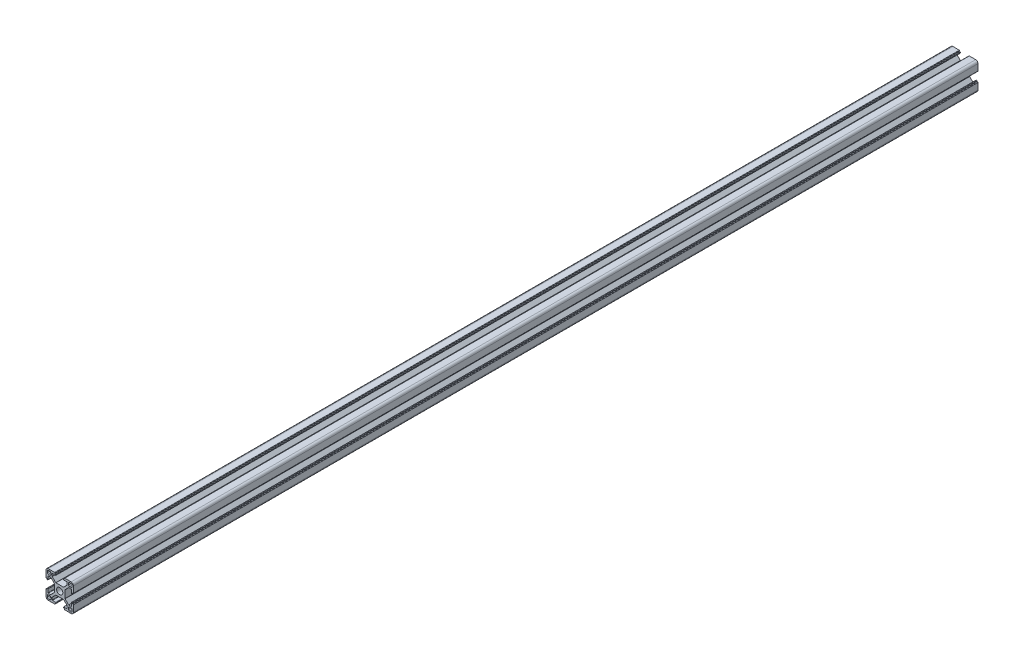
SolidWorks part; units mm, degrees
ref_plane "Front Plane" through (0, 0, 0) normal (0, 0, 1) x (1, 0, 0)
ref_plane "Top Plane" through (0, 0, 0) normal (0, 1, 0) x (1, 0, 0)
ref_plane "Right Plane" through (0, 0, 0) normal (1, 0, 0) x (0, 0, -1)
sketch "Model" plane through (0, 0, 0) normal (0, 0, 1) x (1, 0, 0)
  line L0 (21.5, 27) -> (25, 27)
  line L1 (27, 25) -> (27, 21.5)
  line L2 (25, 19.5) -> (21.5, 19.5)
  line L3 (19.5, 21.5) -> (19.5, 25)
  line L4 (21.5, -27) -> (25, -27)
  line L5 (27, -25) -> (27, -21.5)
  line L6 (25, -19.5) -> (21.5, -19.5)
  line L7 (19.5, -21.5) -> (19.5, -25)
  line L8 (0, 11.6) -> (-8.2402, 11.6)
  line L9 (-8.6645, 11.7757) -> (-16.3243, 19.4355)
  line L10 (-16.5, 19.8598) -> (-16.5, 25)
  line L11 (-15.9, 25.6) -> (-8.8, 25.6)
  line L12 (-8.2, 26.2) -> (-8.2, 27.4)
  line L13 (-8.8, 28) -> (-9.8, 28)
  line L14 (-10.4, 28.6) -> (-10.4, 29.4)
  line L15 (-11, 30) -> (-25, 30)
  line L16 (-30, 25) -> (-30, 11)
  line L17 (-29.4, 10.4) -> (-28.6, 10.4)
  line L18 (-28, 9.8) -> (-28, 8.8)
  line L19 (-27.4, 8.2) -> (-26.2, 8.2)
  line L20 (-25.6, 8.8) -> (-25.6, 15.9)
  line L21 (-25, 16.5) -> (-19.8598, 16.5)
  line L22 (-19.4355, 16.3243) -> (-11.7757, 8.6645)
  line L23 (-11.6, 8.2402) -> (-11.6, 0)
  line L24 (-11.6, 0) -> (-11.6, -8.2402)
  line L25 (-11.7757, -8.6645) -> (-19.4355, -16.3243)
  line L26 (-19.8598, -16.5) -> (-25, -16.5)
  line L27 (-25.6, -15.9) -> (-25.6, -8.8)
  line L28 (-26.2, -8.2) -> (-27.4, -8.2)
  line L29 (-28, -8.8) -> (-28, -9.8)
  line L30 (-28.6, -10.4) -> (-29.4, -10.4)
  line L31 (-30, -11) -> (-30, -25)
  line L32 (-25, -30) -> (-11, -30)
  line L33 (-10.4, -29.4) -> (-10.4, -28.6)
  line L34 (-9.8, -28) -> (-8.8, -28)
  line L35 (-8.2, -27.4) -> (-8.2, -26.2)
  line L36 (-8.8, -25.6) -> (-15.9, -25.6)
  line L37 (-16.5, -25) -> (-16.5, -19.8598)
  line L38 (-16.3243, -19.4355) -> (-8.6645, -11.7757)
  line L39 (-8.2402, -11.6) -> (0, -11.6)
  line L40 (0, -11.6) -> (8.2402, -11.6)
  line L41 (8.6645, -11.7757) -> (16.3243, -19.4355)
  line L42 (16.5, -19.8598) -> (16.5, -25)
  line L43 (15.9, -25.6) -> (8.8, -25.6)
  line L44 (8.2, -26.2) -> (8.2, -27.4)
  line L45 (8.8, -28) -> (9.8, -28)
  line L46 (10.4, -28.6) -> (10.4, -29.4)
  line L47 (11, -30) -> (25, -30)
  line L48 (30, -25) -> (30, -11)
  line L49 (29.4, -10.4) -> (28.6, -10.4)
  line L50 (28, -9.8) -> (28, -8.8)
  line L51 (27.4, -8.2) -> (26.2, -8.2)
  line L52 (25.6, -8.8) -> (25.6, -15.9)
  line L53 (25, -16.5) -> (19.8598, -16.5)
  line L54 (19.4355, -16.3243) -> (11.7757, -8.6645)
  line L55 (11.6, -8.2402) -> (11.6, 0)
  line L56 (11.6, 0) -> (11.6, 8.2402)
  line L57 (11.7757, 8.6645) -> (19.6113, 16.5)
  line L58 (19.6113, 16.5) -> (25, 16.5)
  line L59 (25.6, 15.9) -> (25.6, 8.8)
  line L60 (26.2, 8.2) -> (27.4, 8.2)
  line L61 (28, 8.8) -> (28, 9.8)
  line L62 (28.6, 10.4) -> (29.4, 10.4)
  line L63 (30, 11) -> (30, 25)
  line L64 (25, 30) -> (11, 30)
  line L65 (10.4, 29.4) -> (10.4, 28.6)
  line L66 (9.8, 28) -> (8.8, 28)
  line L67 (8.2, 27.4) -> (8.2, 26.2)
  line L68 (8.8, 25.6) -> (15.9, 25.6)
  line L69 (16.5, 25) -> (16.5, 19.8598)
  line L70 (16.3243, 19.4355) -> (8.6645, 11.7757)
  line L71 (8.2402, 11.6) -> (0, 11.6)
  line L72 (-21.5, -27) -> (-25, -27)
  line L73 (-27, -25) -> (-27, -21.5)
  line L74 (-25, -19.5) -> (-21.5, -19.5)
  line L75 (-19.5, -21.5) -> (-19.5, -25)
  line L76 (-21.5, 27) -> (-25, 27)
  line L77 (-27, 25) -> (-27, 21.5)
  line L78 (-25, 19.5) -> (-21.5, 19.5)
  line L79 (-19.5, 21.5) -> (-19.5, 25)
  circle A0 centre (0, 0) radius 6.8
  arc A1 (21.5, 27) -> (19.5, 25) centre (21.5, 25) ccw
  arc A2 (27, 25) -> (25, 27) centre (25, 25) ccw
  arc A3 (25, 19.5) -> (27, 21.5) centre (25, 21.5) ccw
  arc A4 (19.5, 21.5) -> (21.5, 19.5) centre (21.5, 21.5) ccw
  arc A5 (19.5, -25) -> (21.5, -27) centre (21.5, -25) ccw
  arc A6 (25, -27) -> (27, -25) centre (25, -25) ccw
  arc A7 (27, -21.5) -> (25, -19.5) centre (25, -21.5) ccw
  arc A8 (21.5, -19.5) -> (19.5, -21.5) centre (21.5, -21.5) ccw
  arc A9 (-8.6645, 11.7757) -> (-8.2402, 11.6) centre (-8.2402, 12.2) ccw
  arc A10 (-16.5, 19.8598) -> (-16.3243, 19.4355) centre (-15.9, 19.8598) ccw
  arc A11 (-15.9, 25.6) -> (-16.5, 25) centre (-15.9, 25) ccw
  arc A12 (-8.8, 25.6) -> (-8.2, 26.2) centre (-8.8, 26.2) ccw
  arc A13 (-8.2, 27.4) -> (-8.8, 28) centre (-8.8, 27.4) ccw
  arc A14 (-10.4, 28.6) -> (-9.8, 28) centre (-9.8, 28.6) ccw
  arc A15 (-10.4, 29.4) -> (-11, 30) centre (-11, 29.4) ccw
  arc A16 (-25, 30) -> (-30, 25) centre (-25, 25) ccw
  arc A17 (-30, 11) -> (-29.4, 10.4) centre (-29.4, 11) ccw
  arc A18 (-28, 9.8) -> (-28.6, 10.4) centre (-28.6, 9.8) ccw
  arc A19 (-28, 8.8) -> (-27.4, 8.2) centre (-27.4, 8.8) ccw
  arc A20 (-26.2, 8.2) -> (-25.6, 8.8) centre (-26.2, 8.8) ccw
  arc A21 (-25, 16.5) -> (-25.6, 15.9) centre (-25, 15.9) ccw
  arc A22 (-19.4355, 16.3243) -> (-19.8598, 16.5) centre (-19.8598, 15.9) ccw
  arc A23 (-11.6, 8.2402) -> (-11.7757, 8.6645) centre (-12.2, 8.2402) ccw
  arc A24 (-11.7757, -8.6645) -> (-11.6, -8.2402) centre (-12.2, -8.2402) ccw
  arc A25 (-19.8598, -16.5) -> (-19.4355, -16.3243) centre (-19.8598, -15.9) ccw
  arc A26 (-25.6, -15.9) -> (-25, -16.5) centre (-25, -15.9) ccw
  arc A27 (-25.6, -8.8) -> (-26.2, -8.2) centre (-26.2, -8.8) ccw
  arc A28 (-27.4, -8.2) -> (-28, -8.8) centre (-27.4, -8.8) ccw
  arc A29 (-28.6, -10.4) -> (-28, -9.8) centre (-28.6, -9.8) ccw
  arc A30 (-29.4, -10.4) -> (-30, -11) centre (-29.4, -11) ccw
  arc A31 (-30, -25) -> (-25, -30) centre (-25, -25) ccw
  arc A32 (-11, -30) -> (-10.4, -29.4) centre (-11, -29.4) ccw
  arc A33 (-9.8, -28) -> (-10.4, -28.6) centre (-9.8, -28.6) ccw
  arc A34 (-8.8, -28) -> (-8.2, -27.4) centre (-8.8, -27.4) ccw
  arc A35 (-8.2, -26.2) -> (-8.8, -25.6) centre (-8.8, -26.2) ccw
  arc A36 (-16.5, -25) -> (-15.9, -25.6) centre (-15.9, -25) ccw
  arc A37 (-16.3243, -19.4355) -> (-16.5, -19.8598) centre (-15.9, -19.8598) ccw
  arc A38 (-8.2402, -11.6) -> (-8.6645, -11.7757) centre (-8.2402, -12.2) ccw
  arc A39 (8.6645, -11.7757) -> (8.2402, -11.6) centre (8.2402, -12.2) ccw
  arc A40 (16.5, -19.8598) -> (16.3243, -19.4355) centre (15.9, -19.8598) ccw
  arc A41 (15.9, -25.6) -> (16.5, -25) centre (15.9, -25) ccw
  arc A42 (8.8, -25.6) -> (8.2, -26.2) centre (8.8, -26.2) ccw
  arc A43 (8.2, -27.4) -> (8.8, -28) centre (8.8, -27.4) ccw
  arc A44 (10.4, -28.6) -> (9.8, -28) centre (9.8, -28.6) ccw
  arc A45 (10.4, -29.4) -> (11, -30) centre (11, -29.4) ccw
  arc A46 (25, -30) -> (30, -25) centre (25, -25) ccw
  arc A47 (30, -11) -> (29.4, -10.4) centre (29.4, -11) ccw
  arc A48 (28, -9.8) -> (28.6, -10.4) centre (28.6, -9.8) ccw
  arc A49 (28, -8.8) -> (27.4, -8.2) centre (27.4, -8.8) ccw
  arc A50 (26.2, -8.2) -> (25.6, -8.8) centre (26.2, -8.8) ccw
  arc A51 (25, -16.5) -> (25.6, -15.9) centre (25, -15.9) ccw
  arc A52 (19.4355, -16.3243) -> (19.8598, -16.5) centre (19.8598, -15.9) ccw
  arc A53 (11.6, -8.2402) -> (11.7757, -8.6645) centre (12.2, -8.2402) ccw
  arc A54 (11.7757, 8.6645) -> (11.6, 8.2402) centre (12.2, 8.2402) ccw
  arc A55 (25.6, 15.9) -> (25, 16.5) centre (25, 15.9) ccw
  arc A56 (25.6, 8.8) -> (26.2, 8.2) centre (26.2, 8.8) ccw
  arc A57 (27.4, 8.2) -> (28, 8.8) centre (27.4, 8.8) ccw
  arc A58 (28.6, 10.4) -> (28, 9.8) centre (28.6, 9.8) ccw
  arc A59 (29.4, 10.4) -> (30, 11) centre (29.4, 11) ccw
  arc A60 (30, 25) -> (25, 30) centre (25, 25) ccw
  arc A61 (11, 30) -> (10.4, 29.4) centre (11, 29.4) ccw
  arc A62 (9.8, 28) -> (10.4, 28.6) centre (9.8, 28.6) ccw
  arc A63 (8.8, 28) -> (8.2, 27.4) centre (8.8, 27.4) ccw
  arc A64 (8.2, 26.2) -> (8.8, 25.6) centre (8.8, 26.2) ccw
  arc A65 (16.5, 25) -> (15.9, 25.6) centre (15.9, 25) ccw
  arc A66 (16.3243, 19.4355) -> (16.5, 19.8598) centre (15.9, 19.8598) ccw
  arc A67 (8.2402, 11.6) -> (8.6645, 11.7757) centre (8.2402, 12.2) ccw
  arc A68 (-21.5, -27) -> (-19.5, -25) centre (-21.5, -25) ccw
  arc A69 (-27, -25) -> (-25, -27) centre (-25, -25) ccw
  arc A70 (-25, -19.5) -> (-27, -21.5) centre (-25, -21.5) ccw
  arc A71 (-19.5, -21.5) -> (-21.5, -19.5) centre (-21.5, -21.5) ccw
  arc A72 (-19.5, 25) -> (-21.5, 27) centre (-21.5, 25) ccw
  arc A73 (-25, 27) -> (-27, 25) centre (-25, 25) ccw
  arc A74 (-27, 21.5) -> (-25, 19.5) centre (-25, 21.5) ccw
  arc A75 (-21.5, 19.5) -> (-19.5, 21.5) centre (-21.5, 21.5) ccw
extrude "Boss-Extrude1" add sketch "Model" along normal blind 1980
scale "Scale1" bodies to scale 101 scale about centroid uniform scaling yes scale factor 0.333333
